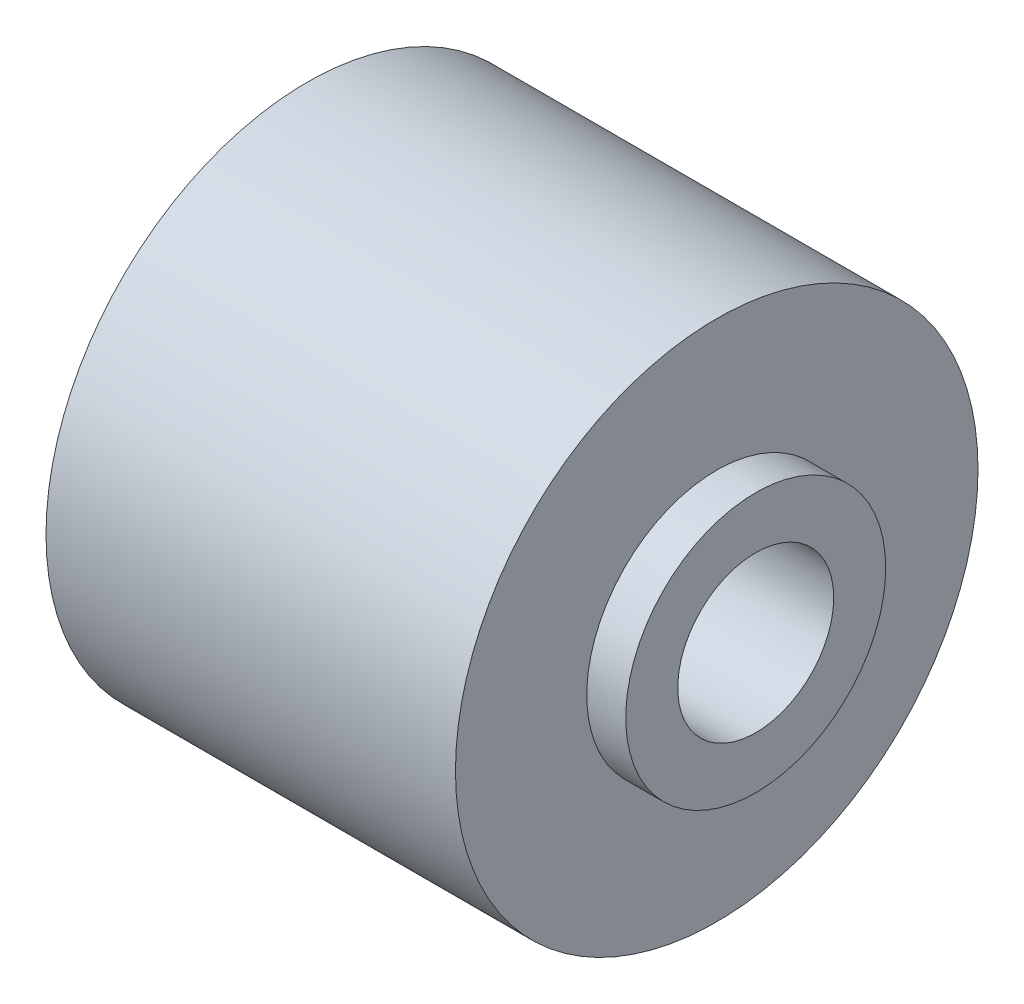
SolidWorks part; units mm, degrees
ref_plane "Płaszczyzna przednia" through (0, 0, 0) normal (0, 0, 1) x (1, 0, 0)
ref_plane "Płaszczyzna górna" through (0, 0, 0) normal (0, 1, 0) x (1, 0, 0)
ref_plane "Płaszczyzna prawa" through (0, 0, 0) normal (1, 0, 0) x (0, 0, -1)
sketch "Szkic1" plane through (0, 0, 0) normal (0, 0, 1) x (1, 0, 0)
  line L0 (0, 0) -> (-39.8849, 0) construction
  line L1 (-15.75, 6) -> (15.75, 6)
  line L2 (-15.75, 6) -> (-15.75, 20.1)
  line L3 (-15.75, 20.1) -> (15.75, 20.1)
  line L4 (15.75, 6) -> (15.75, 20.1)
  line L5 (-15.75, 6) -> (15.75, 20.1) construction
  line L6 (-15.75, 20.1) -> (15.75, 6) construction
  line L7 (-15.75, 6) -> (-18.75, 6)
  line L8 (-15.75, 6) -> (-15.75, 10)
  line L9 (-15.75, 10) -> (-18.75, 10)
  line L10 (-18.75, 6) -> (-18.75, 10)
  line L11 (15.75, 6) -> (18.75, 6)
  line L12 (15.75, 6) -> (15.75, 10)
  line L13 (15.75, 10) -> (18.75, 10)
  line L14 (18.75, 6) -> (18.75, 10)
  point P0 (0, 13.05)
  dimension "D1" = 31.5
  dimension "D2" = 14.1
  dimension "D3" = 6
  dimension "D4" = 4
  dimension "D5" = 3
  dimension "D6" = 3
  dimension "D7" = 4
revolve "Obrót1" add sketch "Szkic1" angle 360 about L0
